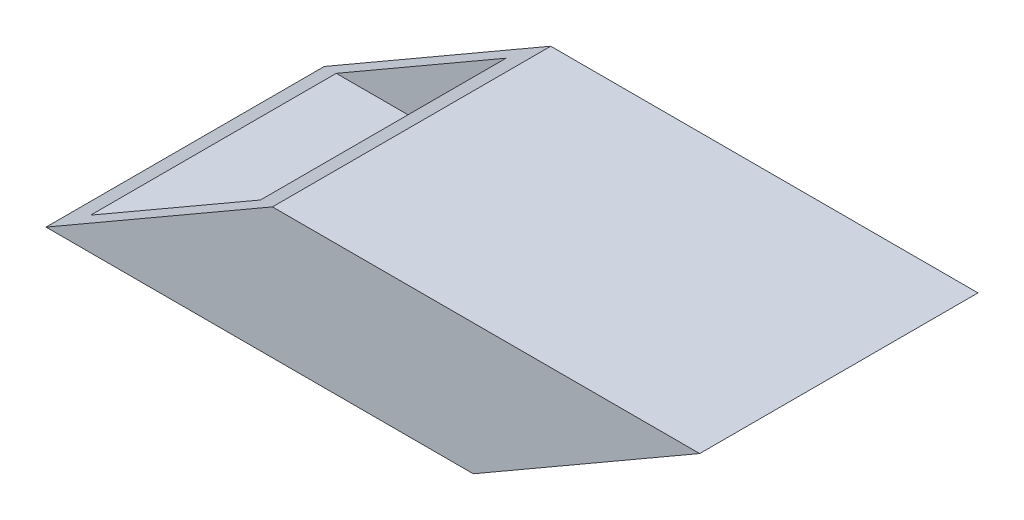
SolidWorks part; units mm, degrees
ref_plane "Front Plane" through (0, 0, 0) normal (0, 0, 1) x (1, 0, 0)
ref_plane "Top Plane" through (0, 0, 0) normal (0, 1, 0) x (1, 0, 0)
ref_plane "Right Plane" through (0, 0, 0) normal (1, 0, 0) x (0, 0, -1)
sketch "Sketch1" plane through (0, 0, 0) normal (1, 0, 0) x (0, 0, -1)
  line L1 (0, 0) -> (42.57, 0)
  line L2 (0, 0) -> (0, 20)
  line L3 (0, 20) -> (42.57, 20)
  line L4 (42.57, 0) -> (42.57, 20)
  dimension "D1" = 42.57
  dimension "D2" = 20
extrude "Boss-Extrude1" add sketch "Sketch1" along normal blind 100
sketch "Sketch2" plane through (0, 0, 0) normal (-1, 0, 0) x (0, 0, 1)
  line L0 (-40.07, 20) -> (-40.07, 17.5) construction
  line L1 (-42.57, 20) -> (0, 20) construction
  line L2 (-40.07, 17.5) -> (-42.57, 17.5) construction
  line L3 (-42.57, 0) -> (-42.57, 20) construction
  line L4 (-42.57, 2.5) -> (-40.07, 2.5) construction
  line L5 (-40.07, 2.5) -> (-40.07, 0) construction
  line L6 (0, 0) -> (-42.57, 0) construction
  line L7 (-2.5, 0) -> (-2.5, 2.5) construction
  line L8 (-2.5, 2.5) -> (0, 2.5) construction
  line L9 (0, 20) -> (0, 0) construction
  line L10 (-2.5, 20) -> (-2.5, 17.5) construction
  line L11 (-2.5, 17.5) -> (0, 17.5) construction
  line L12 (-40.07, 2.5) -> (-40.07, 17.5)
  line L13 (-40.07, 17.5) -> (-2.5, 17.5)
  line L14 (-2.5, 17.5) -> (-2.5, 2.5)
  line L15 (-2.5, 2.5) -> (-40.07, 2.5)
  dimension "D1" = 2.5
  dimension "D2" = 2.5
  dimension "D3" = 2.5
  dimension "D4" = 2.5
  dimension "D5" = 2.5
  dimension "D6" = 2.5
  dimension "D7" = 2.5
  dimension "D8" = 2.5
extrude "Cut-Extrude1" cut sketch "Sketch2" against normal through all
sketch "Sketch3" plane through (0, 0, 0) normal (0, 0, 1) x (1, 0, 0)
  line L0 (0, 0) -> (34.641, 20)
  line L1 (100, 20) -> (0, 20) construction
  line L2 (100, 20) -> (65.359, 0)
  line L3 (100, 0) -> (0, 0) construction
  line L4 (34.641, 20) -> (0, 20)
  line L5 (0, 20) -> (0, 0)
  line L6 (100, 20) -> (100, 0)
  line L7 (100, 0) -> (65.359, 0)
  dimension "D1" = 30
  dimension "D2" = 30
  dimension "D3" = 65.359
extrude "Cut-Extrude2" cut sketch "Sketch3" against normal through all contours L5 L0 L4 | L7 L2 L6
